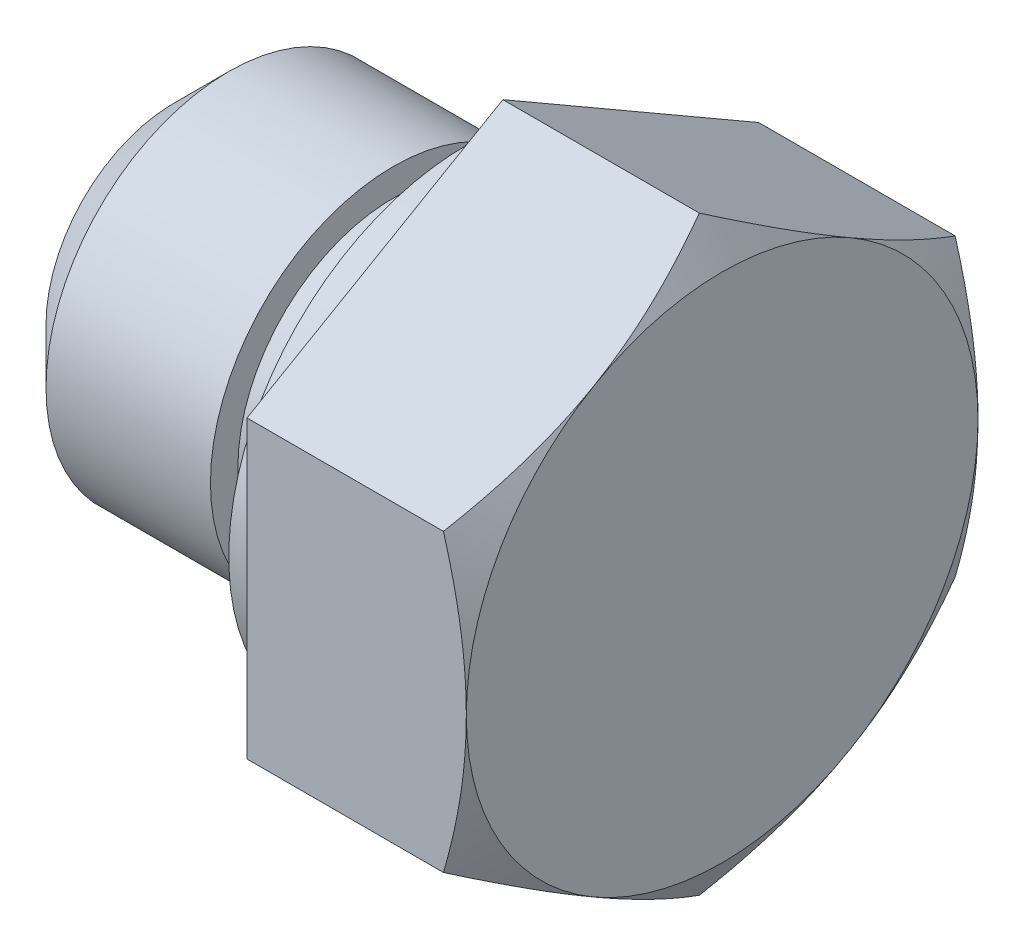
SolidWorks part; units mm, degrees
material "AISI 1045 钢，冷拔"
ref_plane "前视基准面" through (0, 0, 0) normal (0, 0, 1) x (1, 0, 0)
ref_plane "上视基准面" through (0, 0, 0) normal (0, 1, 0) x (1, 0, 0)
ref_plane "右视基准面" through (0, 0, 0) normal (1, 0, 0) x (0, 0, -1)
sketch "草图1" plane through (0, 0, 0) normal (1, 0, 0) x (0, 0, -1)
  line L0 (-10.0792, 0) -> (25.6464, 0) construction
  line L1 (0, 10.0254) -> (0, -11.6395) construction
  line L2 (0, 8.0829) -> (7, 4.0415)
  line L3 (7, 4.0415) -> (7, -4.0415)
  line L4 (7, -4.0415) -> (0, -8.0829)
  line L5 (-7, -4.0415) -> (0, -8.0829)
  line L6 (-7, 4.0415) -> (-7, -4.0415)
  line L7 (0, 8.0829) -> (-7, 4.0415)
  circle A0 centre (0, 0) radius 7 construction
  dimension "D1" = 14
  dimension "D2" = 120
extrude "凸台-拉伸1" add sketch "草图1" against normal blind 6
sketch "草图3" plane through (0, 0, 0) normal (0, 0, 1) x (1, 0, 0)
  line L0 (10.6119, 0) -> (-21.104, 0) construction
  line L1 (-6, 6.5) -> (-7, 6.5)
  line L2 (-6, 4.0415) -> (-6, 8.0829) construction
  line L3 (-7, 6.5) -> (-7, 4.25)
  line L4 (-7, 4.25) -> (-9, 4.25)
  line L5 (-9, 4.25) -> (-9, 5)
  line L6 (-9, 5) -> (-15, 5)
  line L7 (-15, 5) -> (-15, 0)
  line L8 (-15, 0) -> (-6, 0)
  line L9 (-6, -4.0415) -> (-6, 4.0415) construction
  line L10 (-6, 0) -> (-6, 6.5)
  line L11 (0, -4.0415) -> (0, 4.0415) construction
  dimension "D1" = 6.5
  dimension "D2" = 4.25
  dimension "D3" = 5
  dimension "D4" = 15
  dimension "D5" = 8
  dimension "D6" = 2
revolve "旋转1" add sketch "草图3" angle 360 about L0
cosmetic thread "装饰螺纹线1" parameters "D2"=8.376
sketch "草图4" plane through (0, 0, 0) normal (0, 0, 1) x (1, 0, 0)
  line L0 (0, 0) -> (0, -7) construction
  line L1 (0, -8.0829) -> (0, -4.0415) construction
  line L2 (0, -7) -> (-1.4677, -9.5421)
  line L3 (-1.4677, -9.5421) -> (2.0474, -9.5421)
  line L4 (2.0474, -9.5421) -> (0, -7)
  dimension "D1" = 7
  dimension "D2" = 30
ref_axis "基准轴1" through (-15, 0, 0) along (1, 0, 0)
revolve "切除-旋转1" cut sketch "草图4" angle 360 about axis through (-15, 0, 0) along (1, 0, 0)
chamfer "倒角1" distance 1.5 angle 45 1 edges at (-15, 0, -5)
